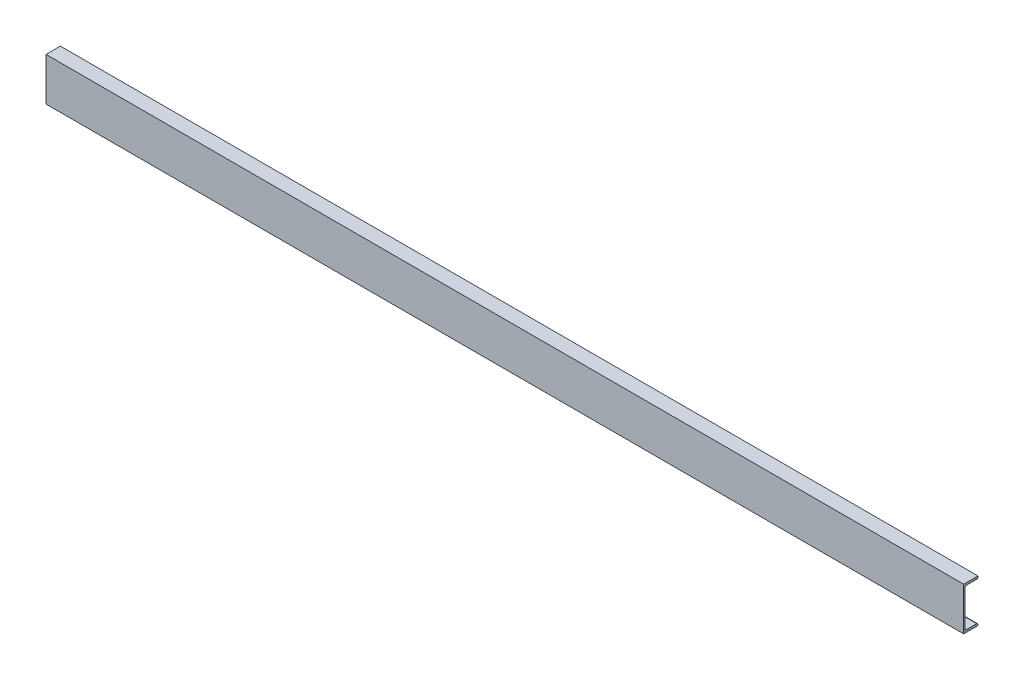
SolidWorks part; units mm, degrees
material "ASTM A36 Steel"
ref_plane "Front Plane" through (0, 0, 0) normal (0, 0, 1) x (1, 0, 0)
ref_plane "Top Plane" through (0, 0, 0) normal (0, 1, 0) x (1, 0, 0)
ref_plane "Right Plane" through (0, 0, 0) normal (1, 0, 0) x (0, 0, -1)
sketch "Sketch1" plane through (0, 0, 0) normal (1, 0, 0) x (0, 0, -1)
  line L0 (-86.6221, 113.8796) -> (-186.6221, 113.8796)
  line L1 (-186.6221, 113.8796) -> (-186.6221, -186.1204)
  line L2 (-186.6221, -186.1204) -> (-86.6221, -186.1204)
  line L3 (-86.6221, -186.1204) -> (-86.6221, -180.1204)
  line L4 (-96.6221, -170.1204) -> (-166.6221, -170.1204)
  line L5 (-176.6221, -160.1204) -> (-176.6221, 87.8796)
  line L6 (-166.6221, 97.8796) -> (-96.6221, 97.8796)
  line L7 (-86.6221, 107.8796) -> (-86.6221, 113.8796)
  arc A0 (-166.6221, -170.1204) -> (-176.6221, -160.1204) centre (-166.6221, -160.1204) cw
  arc A1 (-86.6221, -180.1204) -> (-96.6221, -170.1204) centre (-96.6221, -180.1204) ccw
  arc A2 (-96.6221, 97.8796) -> (-86.6221, 107.8796) centre (-96.6221, 107.8796) ccw
  arc A3 (-176.6221, 87.8796) -> (-166.6221, 97.8796) centre (-166.6221, 87.8796) cw
  point P12 (-86.6221, -170.1204)
  point P15 (-86.6221, 97.8796)
  dimension "D7" = 10
  dimension "D1" = 300
  dimension "D2" = 100
  dimension "D3" = 100
  dimension "D4" = 10
  dimension "D5" = 16
  dimension "D6" = 16
extrude "Boss-Extrude1" add sketch "Sketch1" along normal blind 6400
